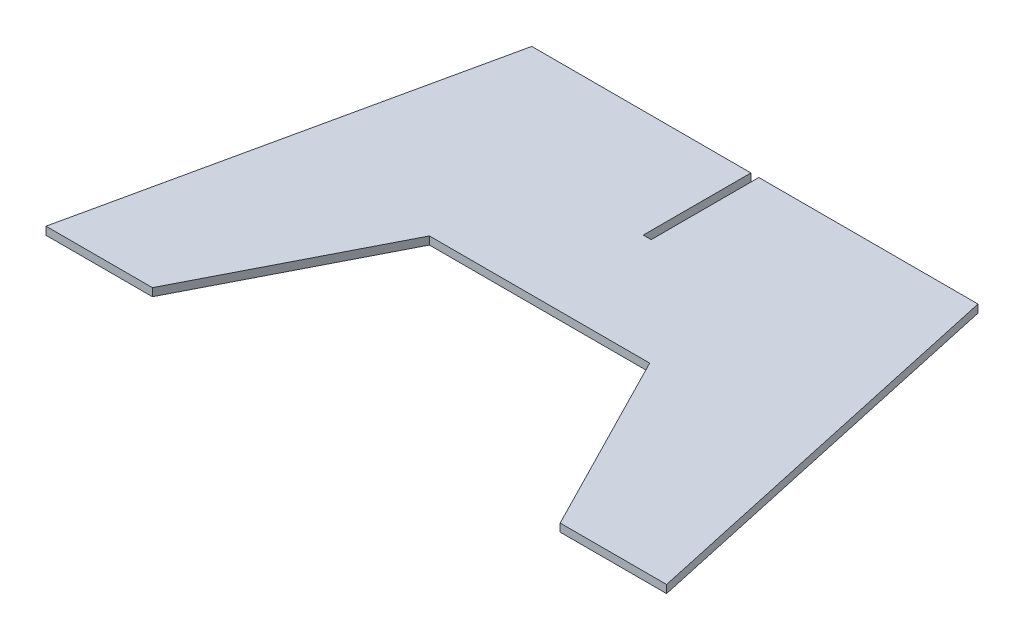
SolidWorks part; units mm, degrees
material "201 Annealed Stainless Steel (SS)"
ref_plane "Front Plane" through (0, 0, 0) normal (0, 0, 1) x (1, 0, 0)
ref_plane "Top Plane" through (0, 0, 0) normal (0, 1, 0) x (1, 0, 0)
ref_plane "Right Plane" through (0, 0, 0) normal (1, 0, 0) x (0, 0, -1)
sketch "Sketch1" plane through (0, 0, 0) normal (0, 1, 0) x (1, 0, 0)
  line L0 (-33.8636, 0) -> (-22.25, 0)
  line L1 (-22.25, 0) -> (-12.0201, 20)
  line L2 (-12.0201, 20) -> (12.0201, 20)
  line L3 (12.0201, 20) -> (22.25, 0)
  line L4 (22.25, 0) -> (33.8636, 0)
  line L5 (33.8636, 0) -> (24.35, 43.5)
  line L6 (24.35, 43.5) -> (-24.35, 43.5)
  line L7 (-24.35, 43.5) -> (-33.8636, 0)
  line L8 (0, 43.5) -> (0, 20) construction
  line L9 (0, 20) -> (0, 0) construction
  line L10 (-22.25, 0) -> (0, 43.5) construction
  line L11 (0, 43.5) -> (22.25, 0) construction
  line L12 (-0.4318, 31.75) -> (-0.4318, 20) construction
  line L13 (-0.4318, 43.5) -> (0.4318, 43.5)
  line L14 (-0.4318, 43.5) -> (-0.4318, 31.75)
  line L15 (-0.4318, 31.75) -> (0.4318, 31.75)
  line L16 (0.4318, 43.5) -> (0.4318, 31.75)
  point P16 (0, 31.75)
  dimension "D1" = 48.7
  dimension "D2" = 43.5
  dimension "D3" = 67.7272
  dimension "D4" = 44.5
  dimension "D5" = 20
  dimension "D6" = 0.8636
extrude "Boss-Extrude1" add sketch "Sketch1" along normal blind 0.8636 contours L6 L16 L15 L14 L7 L0 L1 L2 L3 L4 L5
